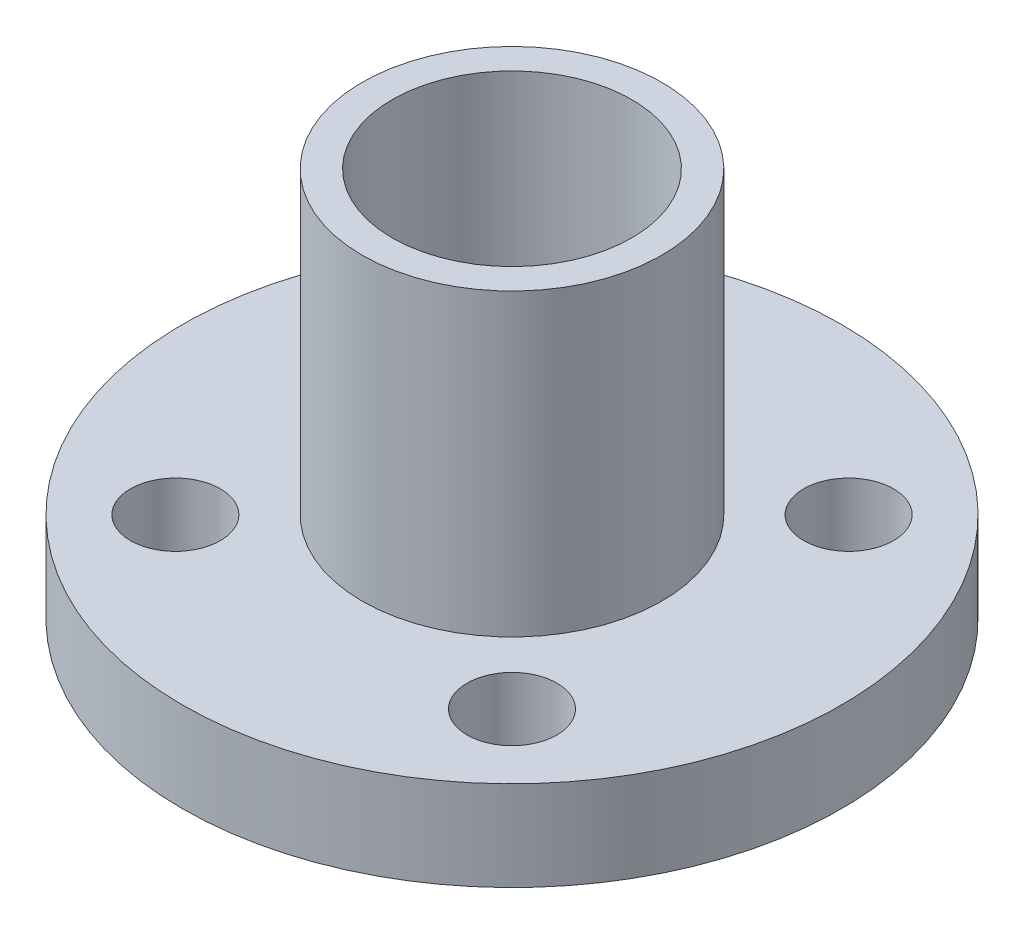
SolidWorks part; units mm, degrees
ref_plane "Front Plane" through (0, 0, 0) normal (0, 0, 1) x (1, 0, 0)
ref_plane "Top Plane" through (0, 0, 0) normal (0, 1, 0) x (1, 0, 0)
ref_plane "Right Plane" through (0, 0, 0) normal (1, 0, 0) x (0, 0, -1)
sketch "Sketch1" plane through (0, 0, 0) normal (0, 1, 0) x (1, 0, 0)
  circle A0 centre (0, 0) radius 11
extrude "Boss-Extrude1" add sketch "Sketch1" along normal blind 3
sketch "Sketch2" plane through (0, 3, 0) normal (0, 1, 0) x (1, 0, 0)
  line L1 (5.6177, -5.6177) -> (-5.6177, -5.6177) construction
  line L2 (5.6177, -5.6177) -> (5.6177, 5.6177) construction
  line L3 (5.6177, 5.6177) -> (-5.6177, 5.6177) construction
  line L4 (-5.6177, -5.6177) -> (-5.6177, 5.6177) construction
  line L5 (5.6177, -5.6177) -> (-5.6177, 5.6177) construction
  line L6 (5.6177, 5.6177) -> (-5.6177, -5.6177) construction
  circle A0 centre (-5.6177, 5.6177) radius 1.5
  circle A1 centre (5.6177, 5.6177) radius 1.5
  circle A2 centre (-5.6177, -5.6177) radius 1.5
  circle A3 centre (5.6177, -5.6177) radius 1.5
  point P0 (0, 0)
extrude "Cut-Extrude1" cut sketch "Sketch2" against normal blind 5
sketch "Sketch3" plane through (0, 3, 0) normal (0, 1, 0) x (1, 0, 0)
  circle A0 centre (0, 0) radius 5
extrude "Boss-Extrude2" add sketch "Sketch3" along normal blind 10
sketch "Sketch4" plane through (0, 13, 0) normal (0, 1, 0) x (1, 0, 0)
  circle A0 centre (0, 0) radius 4
extrude "Cut-Extrude2" cut sketch "Sketch4" against normal through all
